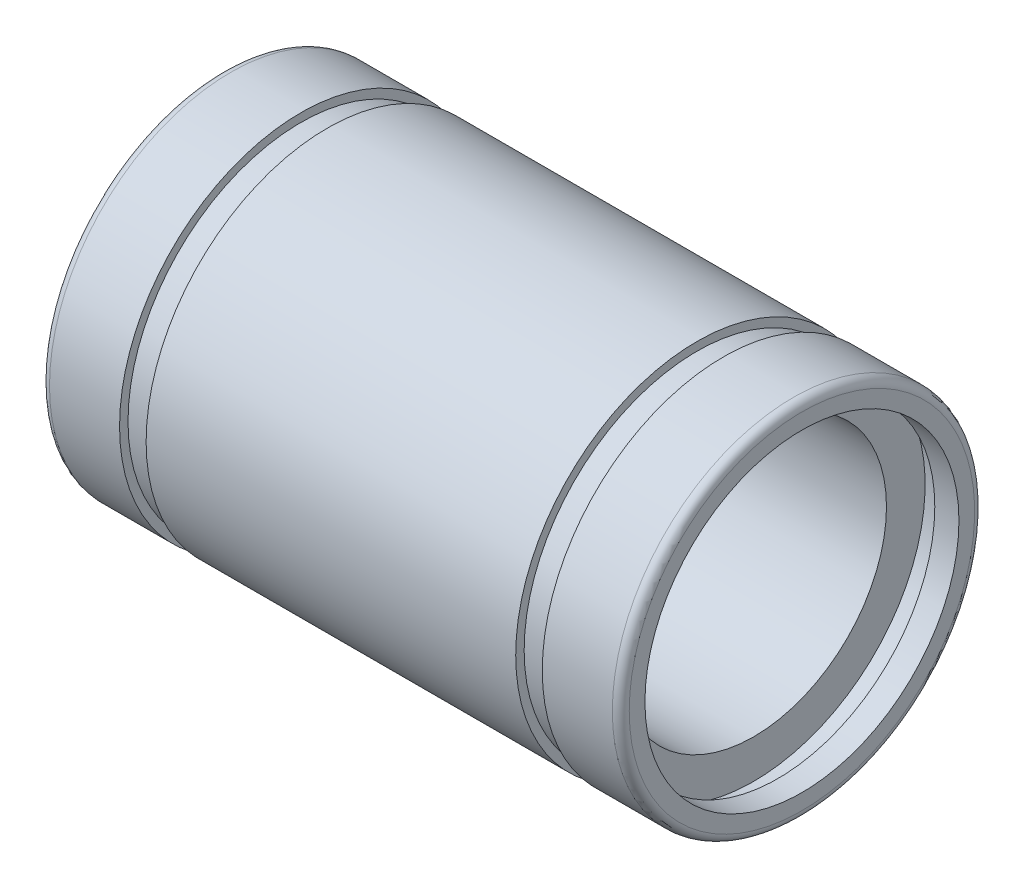
SolidWorks part; units mm, degrees
material "6061-O (SS)"
ref_plane "Alzado" through (0, 0, 0) normal (0, 0, 1) x (1, 0, 0)
ref_plane "Planta" through (0, 0, 0) normal (0, 1, 0) x (1, 0, 0)
ref_plane "Vista lateral" through (0, 0, 0) normal (1, 0, 0) x (0, 0, -1)
sketch "Croquis1" plane through (0, 0, 0) normal (0, 0, 1) x (1, 0, 0)
  line L0 (0, 0) -> (24, 0) construction
  line L1 (24, 7.15) -> (24, 6.5)
  line L2 (20.75, 7.15) -> (19.65, 7.15)
  line L3 (20.75, 7.5) -> (20.75, 7.15)
  line L4 (19.65, 7.15) -> (19.65, 7.5)
  line L5 (19.65, 7.5) -> (4.35, 7.5)
  line L6 (20.75, 7.5) -> (23.65, 7.5)
  line L7 (4.35, 7.5) -> (4.35, 7.15)
  line L8 (4.35, 7.15) -> (3.25, 7.15)
  line L9 (3.25, 7.15) -> (3.25, 7.5)
  line L10 (3.25, 7.5) -> (0.35, 7.5)
  line L11 (0, 7.15) -> (0, 6.5)
  line L12 (2, 5.5) -> (22, 5.5)
  line L13 (22, 5.5) -> (22, 7.1)
  line L14 (22, 7.1) -> (23, 7.1)
  line L15 (23, 7.1) -> (23, 6.5)
  line L16 (23, 6.5) -> (24, 6.5)
  line L17 (2, 6.8) -> (2, 5.5)
  line L18 (2, 6.8) -> (1, 6.8)
  line L19 (1, 6.8) -> (1, 6.5)
  line L20 (1, 6.5) -> (0, 6.5)
  arc A0 (24, 7.15) -> (23.65, 7.5) centre (23.65, 7.15) ccw
  arc A1 (0, 7.15) -> (0.35, 7.5) centre (0.35, 7.15) cw
  point P18 (0, 7.5)
  dimension "D11" = 0.35
  dimension "D12" = 0.35
  dimension "D14" = 2
  dimension "D15" = 1.3
  dimension "D2" = 17.5
  dimension "D3" = 3.25
  dimension "D4" = 1.1
  dimension "D5" = 1.1
  dimension "D6" = 15.3
  dimension "D7" = 24
  dimension "D8" = 6.5
  dimension "D9" = 0.35
  dimension "D10" = 0.35
  dimension "D13" = 1
  dimension "D16" = 1
  dimension "D17" = 1
  dimension "D18" = 0.3
  dimension "D19" = 1.6
  dimension "D20" = 1
  dimension "D21" = 1
  dimension "D22" = 3.25
  dimension "D23" = 7.15
  dimension "D24" = 7.15
  dimension "D25" = 6.5
  dimension "D26" = 22
revolve "Revolución1" add sketch "Croquis1" angle 360 about L0
